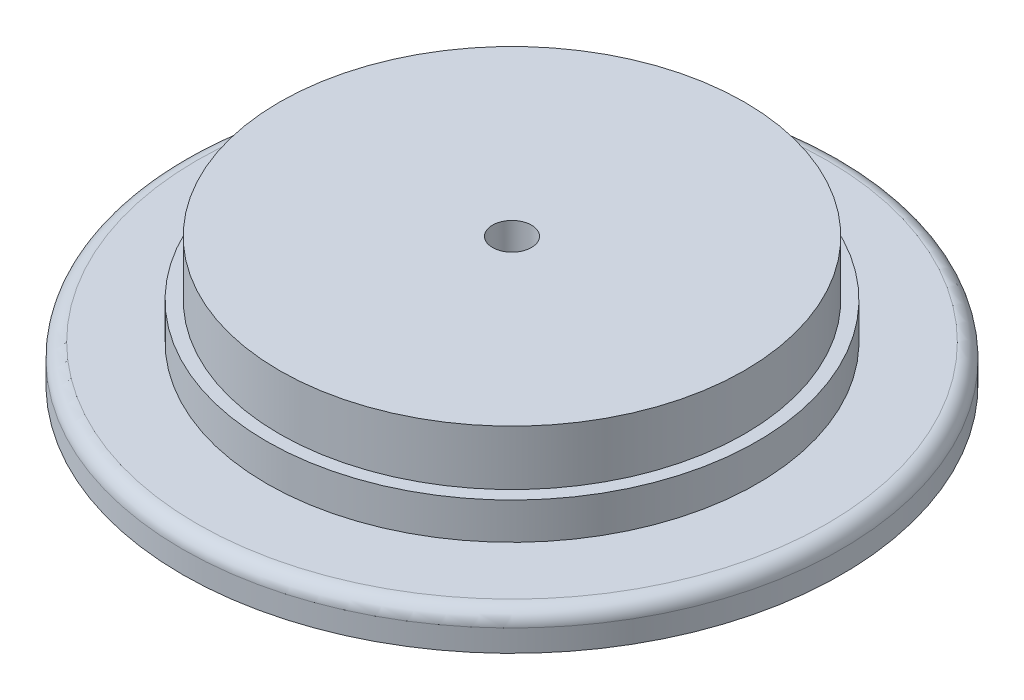
SolidWorks part; units mm, degrees
ref_plane "Front Plane" through (0, 0, 0) normal (0, 0, 1) x (1, 0, 0)
ref_plane "Top Plane" through (0, 0, 0) normal (0, 1, 0) x (1, 0, 0)
ref_plane "Right Plane" through (0, 0, 0) normal (1, 0, 0) x (0, 0, -1)
sketch "Sketch1" plane through (0, 0, 0) normal (0, 1, 0) x (1, 0, 0)
  circle A0 centre (0, 0) radius 40.3225
  dimension "D1" = 80.645
extrude "Boss-Extrude1" add sketch "Sketch1" along normal blind 9.525
sketch "Sketch2" plane through (0, 0, 0) normal (0, -1, 0) x (1, 0, 0)
  circle A0 centre (0, 0) radius 42.545
  dimension "D1" = 85.09
extrude "Boss-Extrude2" add sketch "Sketch2" along normal blind 6.35
sketch "Sketch3" plane through (0, -6.35, 0) normal (0, -1, 0) x (1, 0, 0)
  circle A0 centre (0, 0) radius 57.15
  dimension "D1" = 114.3
extrude "Boss-Extrude3" add sketch "Sketch3" along normal blind 6.35
fillet "Fillet2" radius 2.54 1 edges at (0, -6.35, -57.15)
sketch "Sketch4" plane through (0, -12.7, 0) normal (0, -1, 0) x (1, 0, 0)
  point P0 (0, 0)
hole_wizard "CSK for 1/4 Flat Head Machine Screw (100)1" positions "3DSketch1" profile "Sketch6" countersink size "1/4" standard "ANSI Inch" end condition up to next
sketch3d "3DSketch1"
  point P0 (0, -12.7, 0)
sketch "Sketch6" plane through (0, -12.7, 0) normal (1, 0, 0) x (0, 0, -1)
  line L0 (0, 0) -> (0, 22.225)
  line L1 (0, 22.225) -> (3.3782, 22.225)
  line L2 (3.3782, 22.225) -> (3.3782, 2.5682)
  line L3 (3.3782, 2.5682) -> (6.4389, 0)
  line L5 (6.4389, 0) -> (0, 0)
  line L6 (-3.3782, 2.5682) -> (-6.4389, 0) construction
  line L11 (0, -6.35) -> (0, 107.95) construction
  dimension "Thru Hole Dia." = 6.7564
  dimension "Thru Hole Depth" = 22.225
  dimension "Near C'Sink Dia." = 12.8778
  dimension "Near C'Sink Angle" = 100
